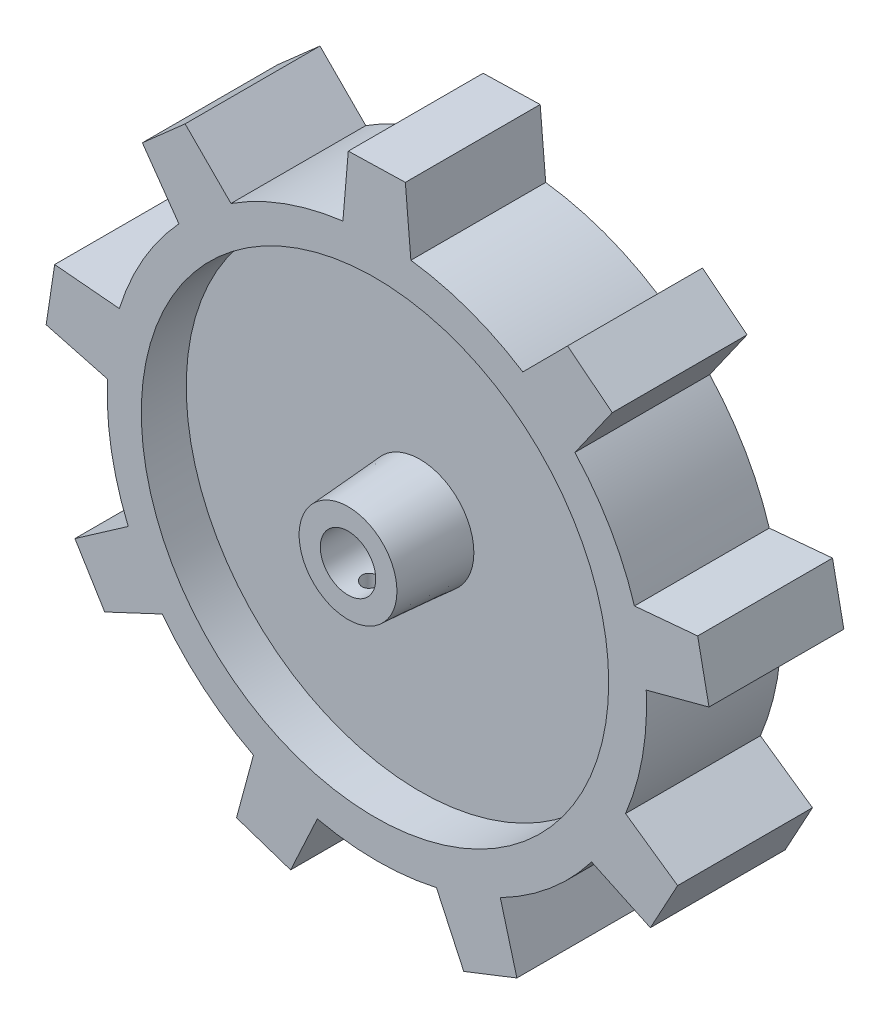
SolidWorks part; units mm, degrees
ref_plane "Front Plane" through (0, 0, 0) normal (0, 0, 1) x (1, 0, 0)
ref_plane "Top Plane" through (0, 0, 0) normal (0, 1, 0) x (1, 0, 0)
ref_plane "Right Plane" through (0, 0, 0) normal (1, 0, 0) x (0, 0, -1)
sketch "Sketch1" plane through (0, 0, 0) normal (0, 0, 1) x (1, 0, 0)
  line L0 (-3.5706, 29.6675) -> (-2.9701, 36.7056)
  line L1 (-2.9701, 36.7056) -> (3.376, 36.8663)
  line L2 (3.376, 36.8663) -> (3.9903, 29.6675)
  line L3 (16.4438, 25.1348) -> (21.4278, 30.1403)
  line L4 (21.4278, 30.1403) -> (26.3925, 26.1842)
  line L5 (26.3925, 26.1842) -> (22.2357, 20.2748)
  line L6 (28.8621, 8.7976) -> (35.8975, 9.4283)
  line L7 (35.8975, 9.4283) -> (37.1578, 3.2066)
  line L8 (37.1578, 3.2066) -> (30.175, 1.3516)
  line L9 (27.8737, -11.6998) -> (33.6686, -15.739)
  line L10 (33.6686, -15.739) -> (30.6348, -21.3152)
  line L11 (30.6348, -21.3152) -> (24.0933, -18.2477)
  line L12 (13.9411, -26.7664) -> (15.7839, -33.5855)
  line L13 (15.7839, -33.5855) -> (9.8756, -35.907)
  line L14 (9.8756, -35.907) -> (6.8362, -29.3524)
  line L15 (-6.4165, -29.3524) -> (-9.388, -35.7606)
  line L16 (-9.388, -35.7606) -> (-15.4064, -33.7412)
  line L17 (-15.4064, -33.7412) -> (-13.5214, -26.7664)
  line L18 (-23.6736, -18.2477) -> (-30.069, -21.2467)
  line L19 (-30.069, -21.2467) -> (-33.3813, -15.8312)
  line L20 (-33.3813, -15.8312) -> (-27.454, -11.6998)
  line L21 (-29.7553, 1.3516) -> (-36.5822, 3.1651)
  line L22 (-36.5822, 3.1651) -> (-35.6386, 9.4427)
  line L23 (-35.6386, 9.4427) -> (-28.4424, 8.7976)
  line L24 (-21.816, 20.2748) -> (-25.88, 26.0523)
  line L25 (-25.88, 26.0523) -> (-21.122, 30.2546)
  line L26 (-21.122, 30.2546) -> (-16.0241, 25.1348)
  arc A0 (-29.7553, 1.3516) -> (-27.454, -11.6998) centre (0.2098, -0.0934) ccw
  arc A1 (-23.6736, -18.2477) -> (-13.5214, -26.7664) centre (0.2098, -0.0934) ccw
  arc A2 (-6.4165, -29.3524) -> (6.8362, -29.3524) centre (0.2098, -0.0934) ccw
  arc A3 (13.9411, -26.7664) -> (24.0933, -18.2477) centre (0.2098, -0.0934) ccw
  arc A4 (27.8737, -11.6998) -> (30.175, 1.3516) centre (0.2098, -0.0934) ccw
  arc A5 (28.8621, 8.7976) -> (22.2357, 20.2748) centre (0.2098, -0.0934) ccw
  arc A6 (16.4438, 25.1348) -> (3.9903, 29.6675) centre (0.2098, -0.0934) ccw
  arc A7 (-3.5706, 29.6675) -> (-16.0241, 25.1348) centre (0.2098, -0.0934) ccw
  arc A8 (-21.816, 20.2748) -> (-28.4424, 8.7976) centre (0.2098, -0.0934) ccw
  point P37 (0, 0)
extrude "Boss-Extrude1" add sketch "Sketch1" along normal blind 15
sketch "Sketch3" plane through (0, 0, 15) normal (0, 0, 1) x (1, 0, 0)
  circle A0 centre (0, 0) radius 26
  dimension "D1" = 52
extrude "Cut-Extrude1" cut sketch "Sketch3" against normal blind 5
sketch "Sketch4" plane through (0, 0, 0) normal (0, 0, -1) x (-1, 0, 0)
  circle A0 centre (0, 0) radius 26
  dimension "D1" = 52
extrude "Cut-Extrude2" cut sketch "Sketch4" against normal blind 5
sketch "Sketch5" plane through (0, 0, 10) normal (0, 0, 1) x (1, 0, 0)
  circle A0 centre (0, 0) radius 6
  dimension "D1" = 12
extrude "Boss-Extrude2" add sketch "Sketch5" along normal blind 8 draft 4
sketch "Sketch6" plane through (0, 0, 5) normal (0, 0, -1) x (-1, 0, 0)
  circle A0 centre (0, 0) radius 6
  dimension "D1" = 12
extrude "Boss-Extrude3" add sketch "Sketch6" along normal blind 5
sketch "Sketch7" plane through (0, 0, 18) normal (0, 0, 1) x (1, 0, 0)
  circle A0 centre (0, 0) radius 3.0842
extrude "Cut-Extrude3" cut sketch "Sketch7" against normal blind 12
sketch "Sketch8" plane through (0, 0, 0) normal (0, 1, 0) x (1, 0, 0)
  circle A0 centre (0, -15.4184) radius 1
  point P2 (0.203, -15)
  point P3 (0.1746, -15.4048)
  point P4 (0, -15.4184)
  point P5 (0, 0)
  point P6 (0.203, -15)
  dimension "D1" = 2
extrude "Cut-Extrude4" cut sketch "Sketch8" against normal up to surface (5.5512 mm away)
